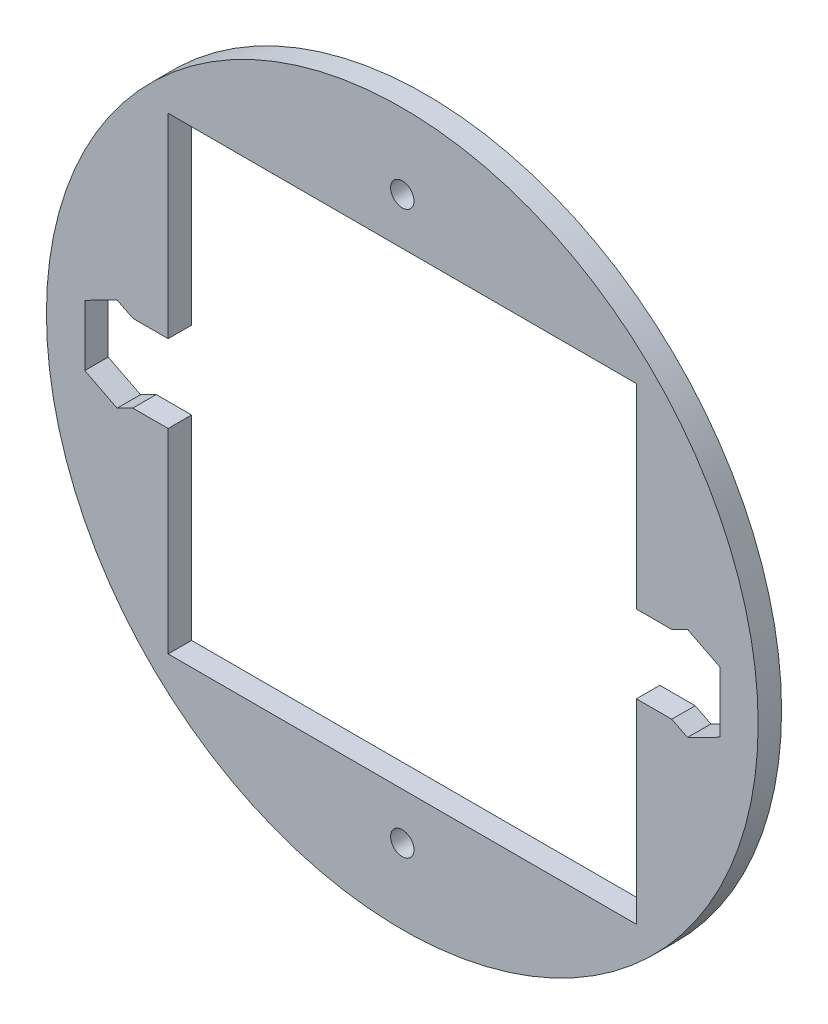
SolidWorks part; units mm, degrees
ref_plane "Front Plane" through (0, 0, 0) normal (0, 0, 1) x (1, 0, 0)
ref_plane "Top Plane" through (0, 0, 0) normal (0, 1, 0) x (1, 0, 0)
ref_plane "Right Plane" through (0, 0, 0) normal (1, 0, 0) x (0, 0, -1)
sketch "Sketch1" plane through (0, 0, 0) normal (0, 0, 1) x (1, 0, 0)
  line L0 (0, -60) -> (0, -67)
  line L1 (-50, 50) -> (50, 50)
  line L2 (-50, 50) -> (-50, -50)
  line L3 (-50, -50) -> (50, -50)
  line L4 (50, 50) -> (50, -50)
  line L5 (-50, 50) -> (50, -50) construction
  line L6 (-50, -50) -> (50, 50) construction
  circle A1 centre (0, 60) radius 2.5
  circle A3 centre (0, -60) radius 2.5
  circle A5 centre (0, 0) radius 76
  dimension "D4" = 60
  dimension "D6" = 152
  dimension "D2" = 100
  dimension "D3" = 100
  dimension "D5" = 50
  dimension "D11" = 50
  dimension "D12" = 7
extrude "circle" add sketch "Sketch1" along normal blind 5 contours A5
sketch "Sketch2" plane through (0, 0, 5) normal (0, 0, 1) x (1, 0, 0)
  line L1 (50, 50) -> (-50, 50)
  line L2 (50, 50) -> (50, -50)
  line L3 (50, -50) -> (-50, -50)
  line L4 (-50, 50) -> (-50, -50)
  line L5 (50, 50) -> (-50, -50) construction
  line L6 (50, -50) -> (-50, 50) construction
  point P0 (0, 0)
  dimension "D1" = 100
  dimension "D2" = 100
extrude "square" cut sketch "Sketch2" against normal blind 5
sketch "Sketch3" plane through (0, 0, 5) normal (0, 0, 1) x (1, 0, 0)
  line L0 (50, -50) -> (50, 50) construction
  circle A0 centre (0, 60) radius 2.5
  circle A1 centre (0, -60) radius 2.5
  circle A3 centre (0, 0) radius 76 construction
  dimension "D1" = 50
  dimension "D2" = 50
  dimension "D3" = 60
  dimension "D4" = 60
extrude "holes" cut sketch "Sketch3" against normal blind 5
sketch "Sketch4" plane through (0, 0, 5) normal (0, 0, 1) x (1, 0, 0)
  line L5 (-50, 0) -> (-50, -8.3)
  line L6 (-50, 50) -> (-50, -50) construction
  line L7 (-50, -8.3) -> (-57.55, -8.3)
  line L8 (-57.55, -8.3) -> (-60.9037, -10)
  line L9 (-60.9037, -10) -> (-67.8072, -6.5)
  line L10 (-67.8072, -6.5) -> (-67.8072, 6.5)
  line L11 (-67.8072, 6.5) -> (-60.9037, 10)
  line L12 (-60.9037, 10) -> (-57.55, 8.3)
  line L13 (-57.55, 8.3) -> (-50, 8.3)
  line L14 (-50, 8.3) -> (-50, 0)
  line L16 (57.55, 8.3) -> (50, 8.3)
  line L17 (60.9037, 10) -> (57.55, 8.3)
  line L18 (67.8072, 6.5) -> (60.9037, 10)
  line L19 (67.8072, -6.5) -> (67.8072, 6.5)
  line L20 (60.9037, -10) -> (67.8072, -6.5)
  line L21 (57.55, -8.3) -> (60.9037, -10)
  line L22 (50, -8.3) -> (57.55, -8.3)
  line L23 (50, 0) -> (50, -8.3)
  line L24 (50, 8.3) -> (50, 0)
  dimension "D1" = 13
  dimension "D2" = 7.74
  dimension "D3" = 7.74
  dimension "D4" = 16.6
  dimension "D5" = 8.3
  dimension "D6" = 8.3
  dimension "D7" = 7.55
  dimension "D8" = 7.55
  dimension "D9" = 3.76
  dimension "D10" = 3.76
  dimension "D11" = 3.5
  dimension "D12" = 1.7
  dimension "D13" = 1.7
  dimension "D14" = 17.8072
  dimension "D15" = 3.5
extrude "Cut-Extrude3" cut sketch "Sketch4" against normal blind 5
